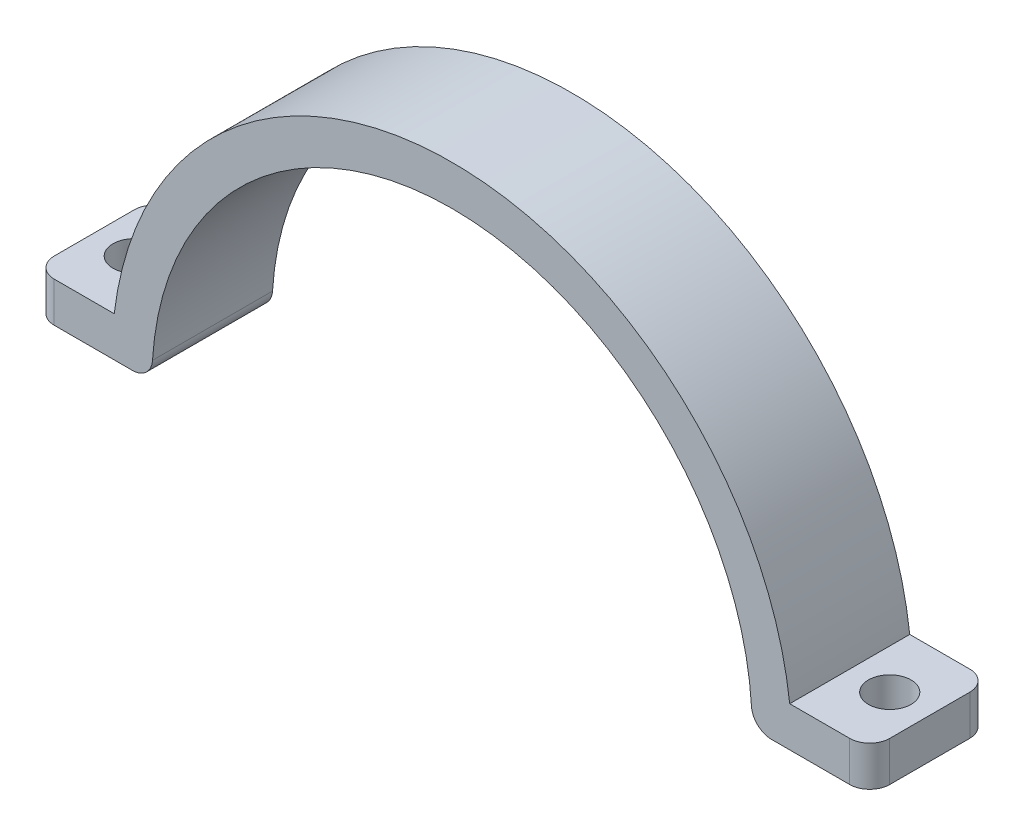
SolidWorks part; units mm, degrees
ref_plane "Front Plane" through (0, 0, 0) normal (0, 0, 1) x (1, 0, 0)
ref_plane "Top Plane" through (0, 0, 0) normal (0, 1, 0) x (1, 0, 0)
ref_plane "Right Plane" through (0, 0, 0) normal (1, 0, 0) x (0, 0, -1)
sketch "Sketch2" plane through (0, 0, 0) normal (0, 0, 1) x (1, 0, 0)
  line L0 (47.625, 0) -> (66.3002, 0)
  line L1 (66.3002, 0) -> (66.3002, 6.35)
  line L2 (66.3002, 6.35) -> (53.6002, 6.35)
  line L3 (0, 0) -> (0, 50000) construction
  line L4 (-66.3002, 6.35) -> (-53.6002, 6.35)
  line L5 (-66.3002, 0) -> (-66.3002, 6.35)
  line L6 (-47.625, 0) -> (-66.3002, 0)
  circle A0 centre (0, 0) radius 44.45 construction
  arc A1 (47.625, 0) -> (-47.625, 0) centre (0, 0) ccw
  arc A2 (53.6002, 6.35) -> (-53.6002, 6.35) centre (0, 0) ccw
  point P9 (5.6344, 53.6801)
  dimension "D1" = 88.9
  dimension "D2" = 53.975
  dimension "D3" = 6.35
  dimension "D4" = 12.7
  dimension "D5" = 6.35
extrude "Boss-Extrude1" add sketch "Sketch2" along normal mid plane 19.05
sketch "Sketch3" plane through (0, 6.35, 0) normal (0, 1, 0) x (1, 0, 0)
  line L0 (66.3002, 9.525) -> (53.6002, 9.525) construction
  line L1 (66.3002, -9.525) -> (66.3002, 9.525) construction
  line L2 (0, 0) -> (0, 50000) construction
  circle A0 centre (59.9502, 0) radius 3.3782
  circle A1 centre (-59.9502, 0) radius 3.3782
  point P4 (59.9502, 9.525)
  point P7 (66.3002, 0)
  dimension "D1" = 6.7564
extrude "Cut-Extrude1" cut sketch "Sketch3" against normal up to next
fillet "Fillet1" radius 3.175 6 edges at (47.625, 0, 0) (-47.625, 0, 0) (66.3002, 3.175, -9.525) (-66.3002, 3.175, -9.525) (-66.3002, 3.175, 9.525) (66.3002, 3.175, 9.525)
